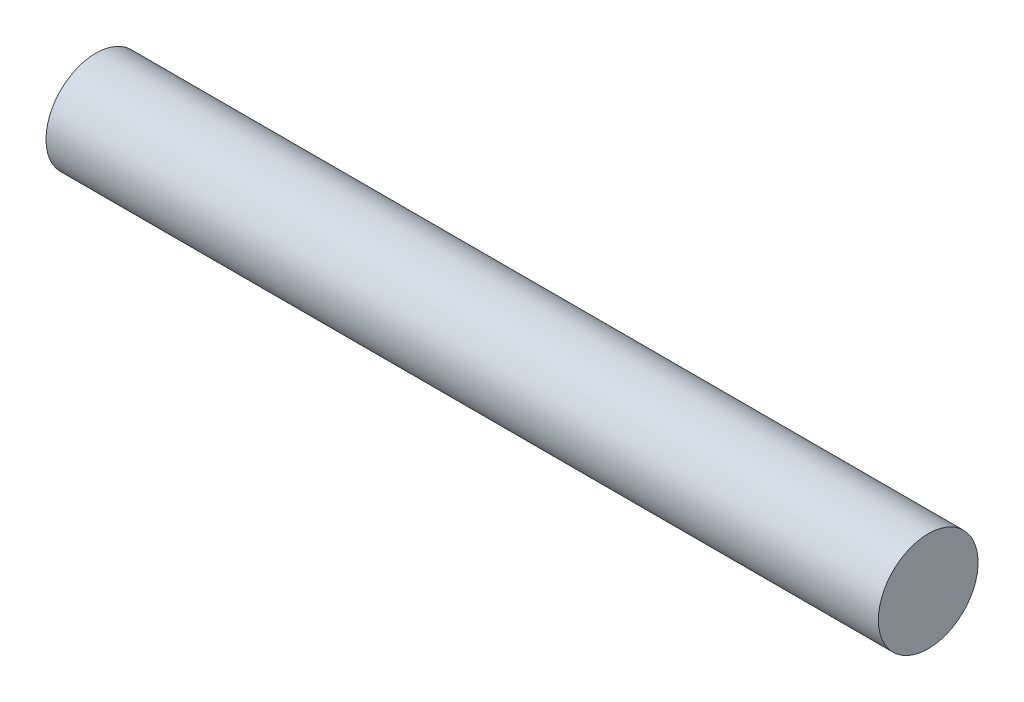
SolidWorks part; units mm, degrees
material "AISI 1035 Steel (SS)"
ref_plane "Front Plane" through (0, 0, 0) normal (0, 0, 1) x (1, 0, 0)
ref_plane "Top Plane" through (0, 0, 0) normal (0, 1, 0) x (1, 0, 0)
ref_plane "Right Plane" through (0, 0, 0) normal (1, 0, 0) x (0, 0, -1)
sketch "Sketch1" plane through (0, 0, 0) normal (1, 0, 0) x (0, 0, -1)
  circle A0 centre (0, 0) radius 4
  dimension "D1" = 8
extrude "Boss-Extrude1" add sketch "Sketch1" along normal blind 45.2
sketch "Sketch2" plane through (0, 0, 0) normal (-1, 0, 0) x (0, 0, 1)
  circle A0 centre (0, 0) radius 4
  dimension "D1" = 8
extrude "Boss-Extrude2" add sketch "Sketch2" along normal blind 21.59
